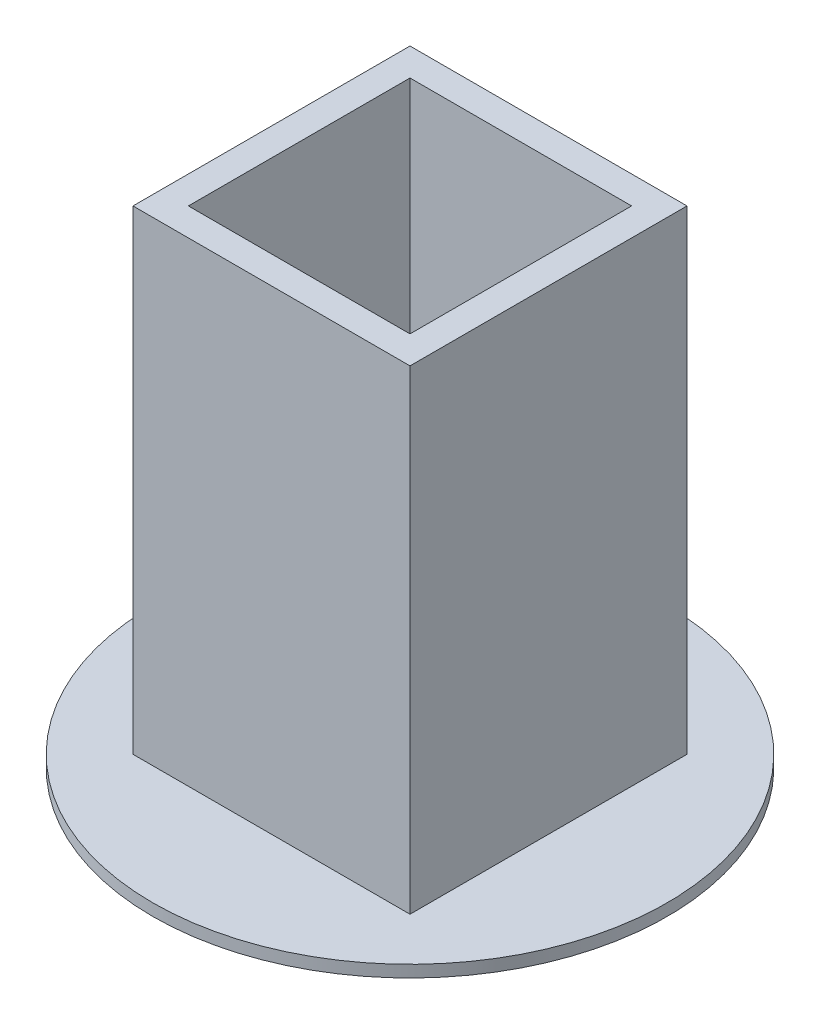
SolidWorks part; units mm, degrees
ref_plane "前视基准面" through (0, 0, 0) normal (0, 0, 1) x (1, 0, 0)
ref_plane "上视基准面" through (0, 0, 0) normal (0, 1, 0) x (1, 0, 0)
ref_plane "右视基准面" through (0, 0, 0) normal (1, 0, 0) x (0, 0, -1)
other "Configuration Table"
sketch "草图1" plane through (0, 0, 0) normal (0, 1, 0) x (1, 0, 0)
  circle A0 centre (0, 0) radius 65
extrude "凸台-拉伸1" add sketch "草图1" along normal blind 3
sketch "草图2" plane through (0, 3, 0) normal (0, 1, 0) x (1, 0, 0)
  line L0 (-35, 35) -> (35, 35)
  line L5 (-35, -35) -> (-35, 35)
  line L6 (-35, -35) -> (35, -35)
  line L7 (35, 35) -> (35, -35)
  point P0 (0, 0)
  point P4 (0, 0)
  point P10 (-35, 0)
extrude "凸台-拉伸2" add sketch "草图2" along normal blind 120
shell "抽壳2" thickness 7
